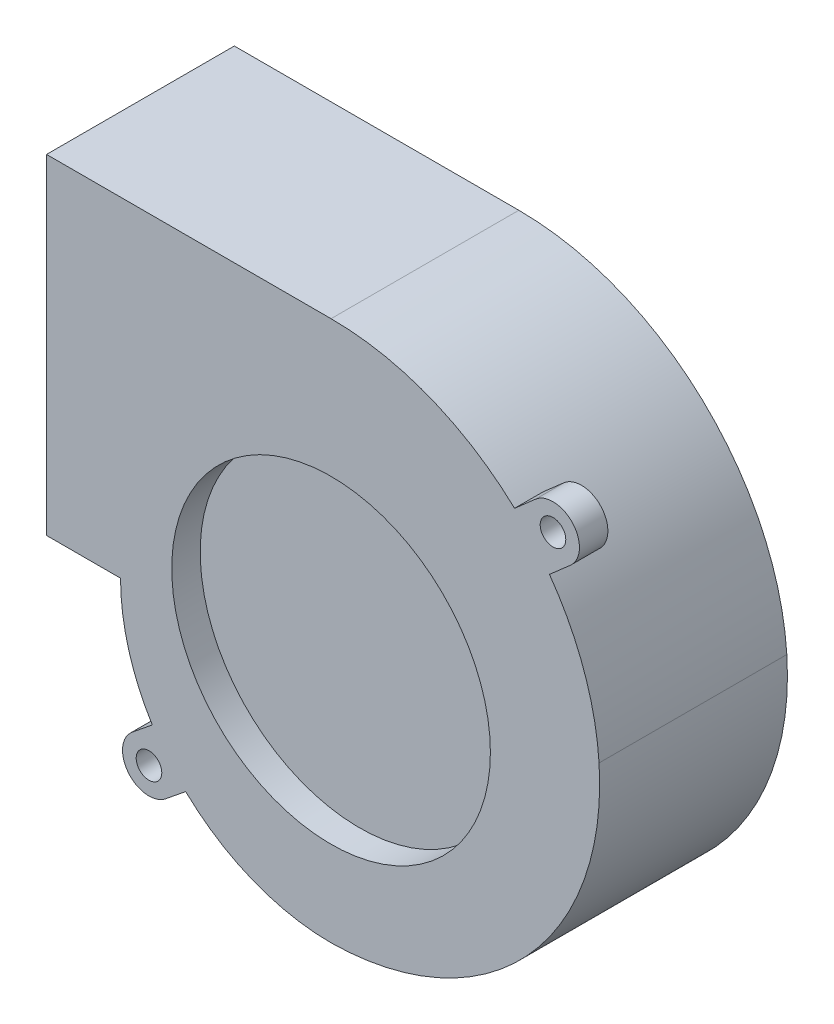
SolidWorks part; units mm, degrees
material "ABS"
ref_plane "Front Plane" through (0, 0, 0) normal (0, 0, 1) x (1, 0, 0)
ref_plane "Top Plane" through (0, 0, 0) normal (0, 1, 0) x (1, 0, 0)
ref_plane "Right Plane" through (0, 0, 0) normal (1, 0, 0) x (0, 0, -1)
sketch "Sketch2" plane through (0, 0, 0) normal (0, 0, 1) x (1, 0, 0)
  line L0 (0, 52) -> (-50, 52)
  line L1 (-50, 52) -> (-50, -6)
  line L2 (-50, -6) -> (-37, -6)
  line L3 (47.1, 58.865) -> (47.1, -43) construction
  line L4 (-47.1, -43) -> (47.1, -43) construction
  line L5 (32.2504, 39.2654) -> (35.9339, 42.496)
  line L6 (38.3825, 32.2735) -> (42.0661, 35.504)
  line L7 (32.2504, 39.2654) -> (38.3825, 32.2735) construction
  line L8 (39, 39) -> (35.3165, 35.7694) construction
  line L9 (-34.9323, -28.3911) -> (-31.4208, -25.538)
  line L10 (-29.0677, -35.6089) -> (-25.5563, -32.7559)
  line L11 (-31.4208, -25.538) -> (-25.5563, -32.7559) construction
  line L12 (-32, -32) -> (-28.4885, -29.1469) construction
  line L13 (-37, -6) -> (-37, -13.5522) construction
  arc A0 (0, 52) -> (47.1, 7.9325) centre (0, 4.7957) cw
  arc A1 (47.1, 7.9325) -> (0, -43) centre (-0.5563, 4.7586) cw
  arc A2 (0, -43) -> (-37, -6) centre (0, -6) cw
  circle A3 centre (0, 0) radius 28
  arc A4 (42.0661, 35.504) -> (35.9339, 42.496) centre (39, 39) ccw
  arc A5 (-34.9323, -28.3911) -> (-29.0677, -35.6089) centre (-32, -32) ccw
  circle A6 centre (39, 39) radius 2.25
  circle A7 centre (-32, -32) radius 2.25
  point P8 (47.1, 7.9325)
  point P12 (0, -43)
  point P21 (-37, -13.5522)
  point P31 (-47.1, -43)
  dimension "D1" = 97.1
  dimension "D6" = 56
  dimension "D11" = 4.5
  dimension "D12" = 4.65
  dimension "D14" = 4.5
  dimension "D2" = 50
  dimension "D3" = 52
  dimension "D4" = 95
  dimension "D5" = 58
  dimension "D7" = 32
  dimension "D8" = 32
  dimension "D9" = 39
  dimension "D10" = 39
extrude "Boss-Extrude1" add sketch "Sketch2" against normal blind 5 contours L6 A4 L5 A0 A6 | L9 A5 L10 A2 A7 | A2 A1 A0 L0 L1 L2 A3
sketch "Sketch5" plane through (0, 0, -5) normal (0, 0, 1) x (1, 0, 0)
  line L0 (0, 52) -> (-50, 52)
  line L1 (-50, 52) -> (-50, -6)
  line L2 (-50, -6) -> (-37, -6)
  line L3 (47.1, 58.865) -> (47.1, -43) construction
  line L4 (-47.1, -43) -> (47.1, -43) construction
  line L5 (32.2504, 39.2654) -> (35.9339, 42.496)
  line L6 (38.3825, 32.2735) -> (42.0661, 35.504)
  line L7 (32.2504, 39.2654) -> (38.3825, 32.2735) construction
  line L8 (39, 39) -> (35.3165, 35.7694) construction
  line L9 (-34.9323, -28.3911) -> (-31.4208, -25.538)
  line L10 (-29.0677, -35.6089) -> (-25.5563, -32.7559)
  line L11 (-31.4208, -25.538) -> (-25.5563, -32.7559) construction
  line L12 (-32, -32) -> (-28.4885, -29.1469) construction
  line L13 (-37, -6) -> (-37, -13.5522) construction
  arc A0 (0, 52) -> (47.1, 7.9325) centre (0, 4.7957) cw
  arc A1 (47.1, 7.9325) -> (0, -43) centre (-0.5563, 4.7586) cw
  arc A2 (0, -43) -> (-37, -6) centre (0, -6) cw
  circle A3 centre (0, 0) radius 28
  arc A4 (42.0661, 35.504) -> (35.9339, 42.496) centre (39, 39) ccw
  arc A5 (-34.9323, -28.3911) -> (-29.0677, -35.6089) centre (-32, -32) ccw
  circle A6 centre (39, 39) radius 2.25
  circle A7 centre (-32, -32) radius 2.25
  point P8 (47.1, 7.9325)
  point P12 (0, -43)
  point P21 (-37, -13.5522)
  point P31 (-47.1, -43)
  arc M32 (38.3825, 32.2735) -> (47.1, 7.9325) centre (0, 4.7957) cw
  arc M33 (47.1, 7.9325) -> (0, -43) centre (-0.5563, 4.7586) cw
  arc M34 (0, -43) -> (-25.5563, -32.7559) centre (0, -6) cw
  arc M38 (-31.4208, -25.538) -> (-37, -6) centre (0, -6) cw
  line M39 (-37, -6) -> (-50, -6)
  line M40 (-50, -6) -> (-50, 52)
  line M41 (-50, 52) -> (0, 52)
  arc M42 (0, 52) -> (32.2504, 39.2654) centre (0, 4.7957) cw
  circle M45 centre (0, 0) radius 28
  dimension "D1" = 97.1
  dimension "D6" = 56
  dimension "D11" = 4.5
  dimension "D12" = 4.65
  dimension "D14" = 4.5
  dimension "D2" = 50
  dimension "D4" = 95
  dimension "D5" = 58
  dimension "D7" = 32
  dimension "D8" = 32
  dimension "D9" = 39
  dimension "D10" = 39
extrude "Boss-Extrude3" add sketch "Sketch5" against normal blind 28 contours A2 A0 M34 M38 M39 M40 M41 M42 M32 M33 M45 | M45
sketch "Sketch6" plane through (-50, 0, 0) normal (-1, 0, 0) x (0, 0, 1)
  line L8 (-31.5, 50.5) -> (-31.5, -4.5)
  line L9 (-31.5, -4.5) -> (-1.5, -4.5)
  line L10 (-1.5, -4.5) -> (-1.5, 50.5)
  line L11 (-1.5, 50.5) -> (-31.5, 50.5)
  line L12 (-31.5, 50.5) -> (-31.5, -4.5)
  line L13 (-31.5, -4.5) -> (-1.5, -4.5)
  line L14 (-1.5, -4.5) -> (-1.5, 50.5)
  line L15 (-1.5, 50.5) -> (-31.5, 50.5)
  dimension "D1" = 1.5
extrude "Cut-Extrude1" cut sketch "Sketch6" against normal blind 20
